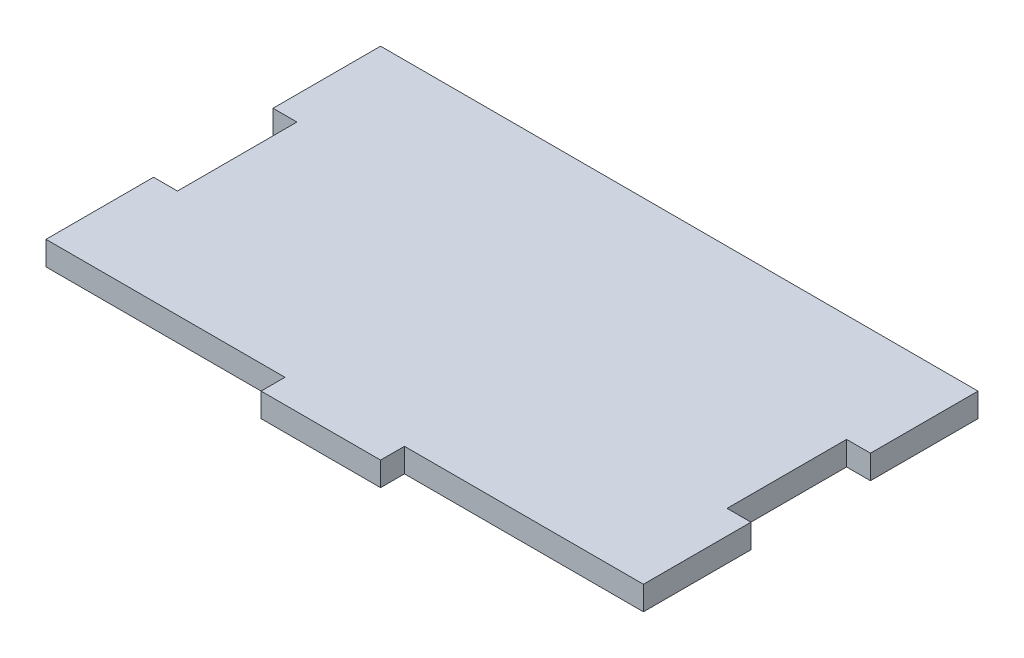
SolidWorks part; units mm, degrees
ref_plane "前视基准面" through (0, 0, 0) normal (0, 0, 1) x (1, 0, 0)
ref_plane "上视基准面" through (0, 0, 0) normal (0, 1, 0) x (1, 0, 0)
ref_plane "右视基准面" through (0, 0, 0) normal (1, 0, 0) x (0, 0, -1)
sketch "草图1" plane through (0, 0, 0) normal (0, 1, 0) x (1, 0, 0)
  line L1 (0, 0) -> (92, 0)
  line L2 (0, 0) -> (0, 56)
  line L3 (0, 56) -> (92, 56)
  line L4 (92, 0) -> (92, 56)
  line L5 (0, 56) -> (-4, 56)
  line L6 (0, 56) -> (0, 38)
  line L7 (0, 38) -> (-4, 38)
  line L8 (-4, 56) -> (-4, 38)
  line L9 (0, 18) -> (-4, 18)
  line L10 (0, 18) -> (0, 0)
  line L11 (0, 0) -> (-4, 0)
  line L12 (-4, 18) -> (-4, 0)
  line L13 (92, 56) -> (96, 56)
  line L14 (92, 56) -> (92, 38)
  line L15 (92, 38) -> (96, 38)
  line L16 (96, 56) -> (96, 38)
  line L17 (92, 18) -> (96, 18)
  line L18 (92, 18) -> (92, 0)
  line L19 (92, 0) -> (96, 0)
  line L20 (96, 18) -> (96, 0)
  line L21 (36, 0) -> (56, 0)
  line L22 (36, 0) -> (36, -4)
  line L23 (36, -4) -> (56, -4)
  line L24 (56, 0) -> (56, -4)
  point P5 (0, 18)
  point P6 (92, 38)
  point P7 (0, 38)
  point P8 (92, 18)
  point P9 (36, 0)
  point P10 (56, 0)
extrude "凸台-拉伸1" add sketch "草图1" along normal blind 4 contours L1 L4 L3 L2 | L9 L12 L11 L2 | L5 L8 L7 L2 | L24 L1 L22 L23 | L20 L17 L4 L19 | L16 L13 L4 L15
